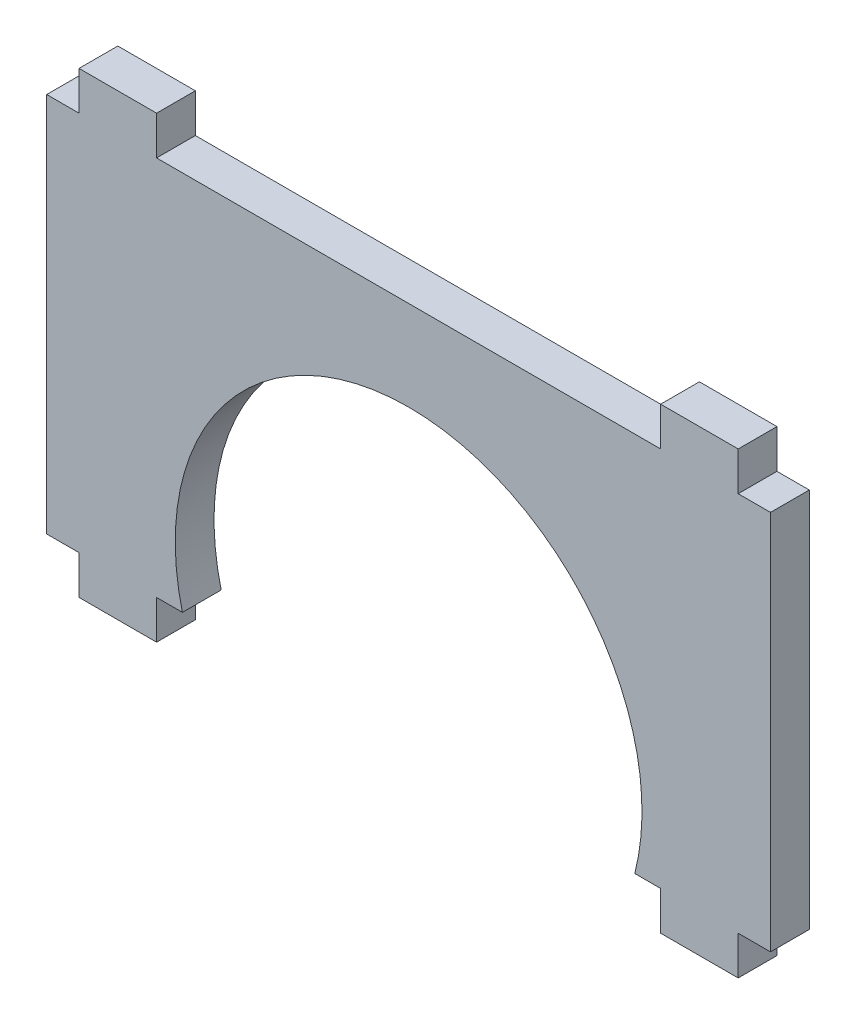
SolidWorks part; units mm, degrees
ref_plane "Front Plane" through (0, 0, 0) normal (0, 0, 1) x (1, 0, 0)
ref_plane "Top Plane" through (0, 0, 0) normal (0, 1, 0) x (1, 0, 0)
ref_plane "Right Plane" through (0, 0, 0) normal (1, 0, 0) x (0, 0, -1)
sketch "Sketch1" plane through (0, 0, 0) normal (0, 0, 1) x (1, 0, 0)
  line L0 (0, 14.725) -> (0, -14.725)
  line L1 (-28, -14.725) -> (28, -14.725)
  line L2 (-28, -14.725) -> (-28, 14.725)
  line L3 (-28, 14.725) -> (28, 14.725)
  line L4 (28, -14.725) -> (28, 14.725)
  line L5 (-28, -14.725) -> (28, 14.725) construction
  line L6 (-28, 14.725) -> (28, -14.725) construction
  line L7 (-25.5, -14.725) -> (-19.5, -14.725)
  line L8 (-25.5, -14.725) -> (-25.5, -17.725)
  line L9 (-25.5, -17.725) -> (-19.5, -17.725)
  line L10 (-19.5, -14.725) -> (-19.5, -17.725)
  line L11 (25.5, -17.725) -> (19.5, -17.725)
  line L12 (19.5, -14.725) -> (19.5, -17.725)
  line L13 (25.5, -14.725) -> (19.5, -14.725)
  line L14 (25.5, -14.725) -> (25.5, -17.725)
  line L15 (-28, 0) -> (28, 0)
  line L16 (25.5, 14.725) -> (25.5, 17.725)
  line L17 (25.5, 14.725) -> (19.5, 14.725)
  line L18 (19.5, 14.725) -> (19.5, 17.725)
  line L19 (25.5, 17.725) -> (19.5, 17.725)
  line L20 (-25.5, 17.725) -> (-19.5, 17.725)
  line L21 (-19.5, 14.725) -> (-19.5, 17.725)
  line L22 (-25.5, 14.725) -> (-19.5, 14.725)
  line L23 (-25.5, 14.725) -> (-25.5, 17.725)
  arc A1 (-17.5, -14.725) -> (17.5, -14.725) centre (0, -10.275) cw
  point P0 (0, 0)
  dimension "D6" = 2
  dimension "D8" = 25
  dimension "D1" = 6
  dimension "D2" = 3
  dimension "D3" = 29.45
  dimension "D4" = 51
  dimension "D5" = 56
  dimension "D7" = 2
extrude "Boss-Extrude1" add sketch "Sketch1" along normal blind 3
